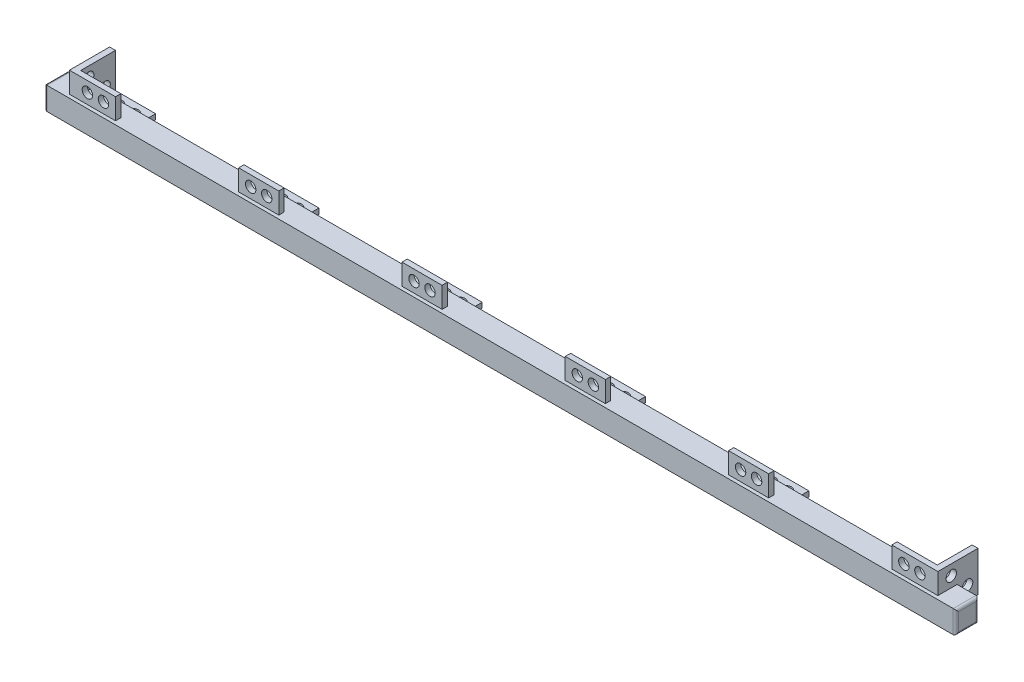
SolidWorks part; units mm, degrees
ref_plane "Front Plane" through (0, 0, 0) normal (0, 0, 1) x (1, 0, 0)
ref_plane "Top Plane" through (0, 0, 0) normal (0, 1, 0) x (1, 0, 0)
ref_plane "Right Plane" through (0, 0, 0) normal (1, 0, 0) x (0, 0, -1)
sketch "Sketch1" plane through (0, 0, 0) normal (1, 0, 0) x (0, 0, -1)
  line L1 (0, 0) -> (8.5, 0)
  line L2 (0, 0) -> (0, 8.5)
  line L3 (0, 8.5) -> (8.5, 8.5)
  line L4 (8.5, 0) -> (8.5, 8.5)
  dimension "D1" = 8.5
  dimension "D2" = 8.5
extrude "Boss-Extrude1" add sketch "Sketch1" along normal blind 340.5
sketch "Sketch2" plane through (0, 8.5, 0) normal (0, 1, 0) x (1, 0, 0)
  line L0 (340.5, 8.5) -> (0, 8.5) construction
  line L1 (6.75, 8.5) -> (333.75, 8.5) construction
  line L2 (6.75, 8.5) -> (6.75, 0) construction
  line L3 (6.75, 0) -> (333.75, 0) construction
  line L4 (333.75, 8.5) -> (333.75, 0) construction
  line L5 (340.5, 0) -> (0, 0) construction
  line L6 (340.5, 8.5) -> (340.5, 0) construction
  line L9 (0, 8.5) -> (0, 0) construction
  line L10 (17.75, 1.3) -> (17.75, 3.3) construction
  line L11 (10.25, 3.3) -> (25.25, 3.3)
  line L12 (10.25, 3.3) -> (10.25, 1.3)
  line L13 (10.25, 1.3) -> (25.25, 1.3)
  line L14 (25.25, 3.3) -> (25.25, 1.3)
  line L15 (71.25, 1.3) -> (86.25, 1.3)
  line L16 (71.25, 3.3) -> (71.25, 1.3)
  line L17 (71.25, 3.3) -> (86.25, 3.3)
  line L18 (86.25, 3.3) -> (86.25, 1.3)
  line L19 (132.25, 1.3) -> (147.25, 1.3)
  line L20 (132.25, 3.3) -> (132.25, 1.3)
  line L21 (132.25, 3.3) -> (147.25, 3.3)
  line L22 (147.25, 3.3) -> (147.25, 1.3)
  line L23 (193.25, 1.3) -> (208.25, 1.3)
  line L24 (193.25, 3.3) -> (193.25, 1.3)
  line L25 (193.25, 3.3) -> (208.25, 3.3)
  line L26 (208.25, 3.3) -> (208.25, 1.3)
  line L27 (254.25, 1.3) -> (269.25, 1.3)
  line L28 (254.25, 3.3) -> (254.25, 1.3)
  line L29 (254.25, 3.3) -> (269.25, 3.3)
  line L30 (269.25, 3.3) -> (269.25, 1.3)
  line L31 (315.25, 1.3) -> (330.25, 1.3)
  line L32 (315.25, 3.3) -> (315.25, 1.3)
  line L33 (315.25, 3.3) -> (330.25, 3.3)
  line L34 (330.25, 3.3) -> (330.25, 1.3)
  point P8 (340.5, 4.25)
  dimension "D1" = 327
  dimension "D2" = 6.75
  dimension "D3" = 6.75
  dimension "D4" = 2
  dimension "D5" = 15
  dimension "D6" = 11
  dimension "D8" = 1.3
  dimension "D7" = 6
extrude "Boss-Extrude2" add sketch "Sketch2" along normal blind 7.8
sketch "Sketch3" plane through (0, 0, -1.3) normal (0, 0, 1) x (1, 0, 0)
  line L0 (10.25, 8.5) -> (25.25, 8.5) construction
  line L3 (10.25, 16.3) -> (10.25, 8.5) construction
  circle A0 centre (14.75, 12.4) radius 1.95
  circle A1 centre (20.75, 12.4) radius 1.95
  circle A2 centre (75.75, 12.4) radius 1.95
  circle A3 centre (81.75, 12.4) radius 1.95
  circle A4 centre (136.75, 12.4) radius 1.95
  circle A5 centre (142.75, 12.4) radius 1.95
  circle A6 centre (197.75, 12.4) radius 1.95
  circle A7 centre (203.75, 12.4) radius 1.95
  circle A8 centre (258.75, 12.4) radius 1.95
  circle A9 centre (264.75, 12.4) radius 1.95
  circle A10 centre (319.75, 12.4) radius 1.95
  circle A11 centre (325.75, 12.4) radius 1.95
  dimension "D6" = 3.9
  dimension "D7" = 3.9
  dimension "D1" = 3.9
  dimension "D2" = 3.9
  dimension "D3" = 6
  dimension "D4" = 4.5
  dimension "D5" = 6
extrude "Cut-Extrude1" cut sketch "Sketch3" against normal blind 7.8
sketch "Sketch4" plane through (0, 0, -8.5) normal (0, 0, -1) x (-1, 0, 0)
  line L0 (-269.25, 1.3) -> (-254.25, 1.3)
  line L1 (-330.25, 3.3) -> (-315.25, 3.3)
  line L2 (-330.25, 3.3) -> (-330.25, 1.3)
  line L3 (-330.25, 1.3) -> (-315.25, 1.3)
  line L4 (-315.25, 3.3) -> (-315.25, 1.3)
  line L5 (-269.25, 3.3) -> (-269.25, 1.3)
  line L6 (-269.25, 3.3) -> (-254.25, 3.3)
  line L7 (-254.25, 3.3) -> (-254.25, 1.3)
  line L8 (-208.25, 1.3) -> (-193.25, 1.3)
  line L9 (-208.25, 3.3) -> (-208.25, 1.3)
  line L10 (-208.25, 3.3) -> (-193.25, 3.3)
  line L11 (-193.25, 3.3) -> (-193.25, 1.3)
  line L12 (-147.25, 1.3) -> (-132.25, 1.3)
  line L13 (-147.25, 3.3) -> (-147.25, 1.3)
  line L14 (-147.25, 3.3) -> (-132.25, 3.3)
  line L15 (-132.25, 3.3) -> (-132.25, 1.3)
  line L16 (-86.25, 1.3) -> (-71.25, 1.3)
  line L17 (-86.25, 3.3) -> (-86.25, 1.3)
  line L18 (-86.25, 3.3) -> (-71.25, 3.3)
  line L19 (-71.25, 3.3) -> (-71.25, 1.3)
  line L20 (-25.25, 1.3) -> (-10.25, 1.3)
  line L21 (-25.25, 3.3) -> (-25.25, 1.3)
  line L22 (-25.25, 3.3) -> (-10.25, 3.3)
  line L23 (-10.25, 3.3) -> (-10.25, 1.3)
  line L25 (-340.5, 0) -> (0, 0) construction
  dimension "D1" = 2
  dimension "D2" = 15
  dimension "D4" = 1.3
  dimension "D3" = 6
extrude "Boss-Extrude3" add sketch "Sketch4" along normal blind 7.8
sketch "Sketch5" plane through (0, 1.3, 0) normal (0, -1, 0) x (1, 0, 0)
  line L0 (330.25, -16.3) -> (330.25, -8.5) construction
  line L2 (330.25, -8.5) -> (315.25, -8.5) construction
  circle A0 centre (325.75, -12.4) radius 1.95
  circle A1 centre (319.75, -12.4) radius 1.95
  circle A2 centre (264.75, -12.4) radius 1.95
  circle A3 centre (258.75, -12.4) radius 1.95
  circle A4 centre (203.75, -12.4) radius 1.95
  circle A5 centre (197.75, -12.4) radius 1.95
  circle A6 centre (142.75, -12.4) radius 1.95
  circle A7 centre (136.75, -12.4) radius 1.95
  circle A8 centre (81.75, -12.4) radius 1.95
  circle A9 centre (75.75, -12.4) radius 1.95
  circle A10 centre (20.75, -12.4) radius 1.95
  circle A11 centre (14.75, -12.4) radius 1.95
  dimension "D1" = 3.9
  dimension "D2" = 3.9
  dimension "D3" = 6
  dimension "D4" = 4.5
  dimension "D6" = 3.9
  dimension "D5" = 6
extrude "Cut-Extrude2" cut sketch "Sketch5" against normal blind 7.8 contours A2 | A3 | A4 | A5 | A6 | A7 | A10 | A11 | A8 | A9 | A0 | A1
fillet "Fillet1" radius 1 4 edges at (340.5, 0, -4.25) (340.5, 4.25, 0) (340.5, 4.25, -8.5) (340.5, 8.5, -4.25)
fillet "Fillet3" radius 1 4 edges at (0, 4.25, 0) (0, 0, -4.25) (0, 4.25, -8.5) (0, 8.5, -4.25)
sketch "Sketch7" plane through (330.25, 0, 0) normal (1, 0, 0) x (0, 0, -1)
  line L0 (1.3, 8.5) -> (8.5, 8.5)
  line L1 (8.5, 8.5) -> (7.5, 7.5) construction
  line L2 (0, 8.5) -> (8.5, 8.5) construction
  line L3 (8.5, 8.5) -> (8.5, 1.3)
  line L4 (8.5, 1.3) -> (16.3, 1.3)
  line L5 (16.3, 1.3) -> (16.3, 16.3)
  line L6 (16.3, 16.3) -> (1.3, 16.3)
  line L7 (1.3, 16.3) -> (1.3, 8.5)
extrude "Boss-Extrude5" add sketch "Sketch7" along normal blind 2.2
sketch "Sketch8" plane through (10.25, 0, 0) normal (-1, 0, 0) x (0, 0, 1)
  line L0 (-1.3, 16.3) -> (-16.3, 16.3)
  line L1 (-16.3, 16.3) -> (-16.3, 1.3)
  line L2 (-16.3, 1.3) -> (-8.5, 1.3)
  line L3 (-8.5, 1.3) -> (-8.5, 8.5)
  line L4 (-8.5, 8.5) -> (-1.3, 8.5)
  line L5 (-1.3, 8.5) -> (-1.3, 16.3)
extrude "Boss-Extrude6" add sketch "Sketch8" along normal blind 2.2
sketch "Sketch9" plane through (8.05, 0, 0) normal (-1, 0, 0) x (0, 0, 1)
  line L0 (-1.3, 16.3) -> (-16.3, 16.3) construction
  line L1 (-16.3, 16.3) -> (-16.3, 1.3) construction
  line L4 (-8.5, 1.3) -> (-8.5, 8.5) construction
  circle A0 centre (-12.4, 6.3) radius 1.95
  circle A1 centre (-6.3, 12.4) radius 1.95
  dimension "D1" = 3.9
  dimension "D2" = 3.9
  dimension "D3" = 10
  dimension "D4" = 10
  dimension "D5" = 3.9
  dimension "D6" = 3.9
extrude "Cut-Extrude3" cut sketch "Sketch9" against normal blind 350
